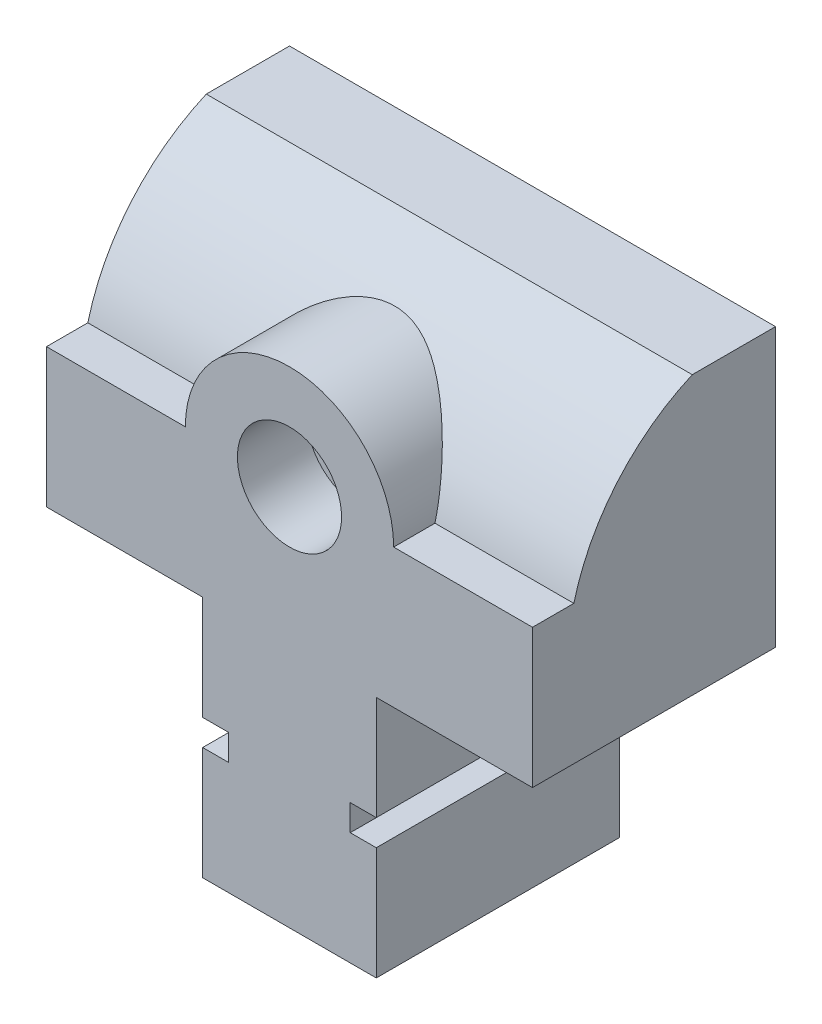
SolidWorks part; units mm, degrees
material "Gray Cast Iron"
ref_plane "Front Plane" through (0, 0, 0) normal (0, 0, 1) x (1, 0, 0)
ref_plane "Top Plane" through (0, 0, 0) normal (0, 1, 0) x (1, 0, 0)
ref_plane "Right Plane" through (0, 0, 0) normal (1, 0, 0) x (0, 0, -1)
sketch "Sketch1" plane through (0, 0, 0) normal (0, 0, 1) x (1, 0, 0)
  line L0 (0, 0) -> (31.75, 0)
  line L1 (31.75, 0) -> (31.75, 44.45)
  line L2 (31.75, 44.45) -> (60.325, 44.45)
  line L3 (60.325, 44.45) -> (60.325, 69.85)
  line L4 (60.325, 69.85) -> (34.925, 69.85)
  line L5 (0, 0) -> (0, 44.45)
  line L6 (0, 44.45) -> (-28.575, 44.45)
  line L7 (-28.575, 44.45) -> (-28.575, 69.85)
  line L8 (-28.575, 69.85) -> (-3.175, 69.85)
  arc A0 (-3.175, 69.85) -> (34.925, 69.85) centre (15.875, 69.85) cw
  dimension "D2" = 19.05
  dimension "D1" = 31.75
  dimension "D3" = 44.45
  dimension "D4" = 25.4
  dimension "D6" = 28.575
  dimension "D7" = 28.575
extrude "Boss-Extrude1" add sketch "Sketch1" against normal blind 44.45
sketch "Sketch2" plane through (-28.575, 0, 0) normal (-1, 0, 0) x (0, 0, 1)
  line L1 (-44.45, 44.45) -> (-44.45, 60.325)
  line L2 (-44.45, 44.45) -> (-9.8148, 44.45)
  line L3 (-44.45, 44.45) -> (0, 44.45) construction
  line L4 (-44.45, 69.85) -> (-7.5598, 69.85)
  line L5 (-44.45, 69.85) -> (0, 69.85) construction
  line L7 (-44.45, 95.25) -> (-29.2232, 95.25)
  line L8 (-7.5598, 69.85) -> (-44.45, 69.85)
  line L9 (-44.45, 69.85) -> (-44.45, 95.25)
  line L10 (-44.45, 95.25) -> (-44.45, 44.45)
  arc A0 (-7.5598, 69.85) -> (-29.2232, 95.25) centre (-44.45, 60.325) ccw
  line M10 (0, 69.85) -> (-44.45, 69.85)
  dimension "D2" = 76.2
  dimension "D1" = 15.875
  dimension "D3" = 50.8
extrude "Boss-Extrude2" add sketch "Sketch2" against normal blind 88.9 contours A0 L7 L9 M10
sketch "Sketch3" plane through (0, 0, 0) normal (0, 0, 1) x (1, 0, 0)
  circle A0 centre (15.875, 69.85) radius 9.525
  dimension "D1" = 19.05
extrude "Cut-Extrude1" cut sketch "Sketch3" against normal blind 12.7
sketch "Sketch4" plane through (0, 0, 0) normal (0, 0, 1) x (1, 0, 0)
  line L0 (0, 44.45) -> (0, 25.4)
  line L1 (0, 44.45) -> (0, 0) construction
  line L2 (0, 25.4) -> (4.7625, 25.4)
  line L3 (4.7625, 25.4) -> (4.7625, 20.6375)
  line L4 (4.7625, 20.6375) -> (0, 20.6375)
  line L5 (0, 20.6375) -> (0, 25.4)
  line L6 (31.75, 44.45) -> (31.75, 25.4)
  line L7 (31.75, 0) -> (31.75, 44.45) construction
  line L8 (31.75, 25.4) -> (26.9875, 25.4)
  line L9 (26.9875, 25.4) -> (26.9875, 20.6375)
  line L10 (26.9875, 20.6375) -> (31.75, 20.6375)
  line L11 (31.75, 20.6375) -> (31.75, 25.4)
  line M8 (0, 44.45) -> (0, 0)
  line M10 (31.75, 0) -> (31.75, 44.45)
  dimension "D1" = 19.05
  dimension "D2" = 19.05
  dimension "D3" = 4.7625
  dimension "D4" = 4.7625
  dimension "D5" = 4.7625
  dimension "D6" = 4.7625
extrude "Cut-Extrude2" cut sketch "Sketch4" against normal through all contours L4 L3 L2 M8 | L9 L10 L8 M10
